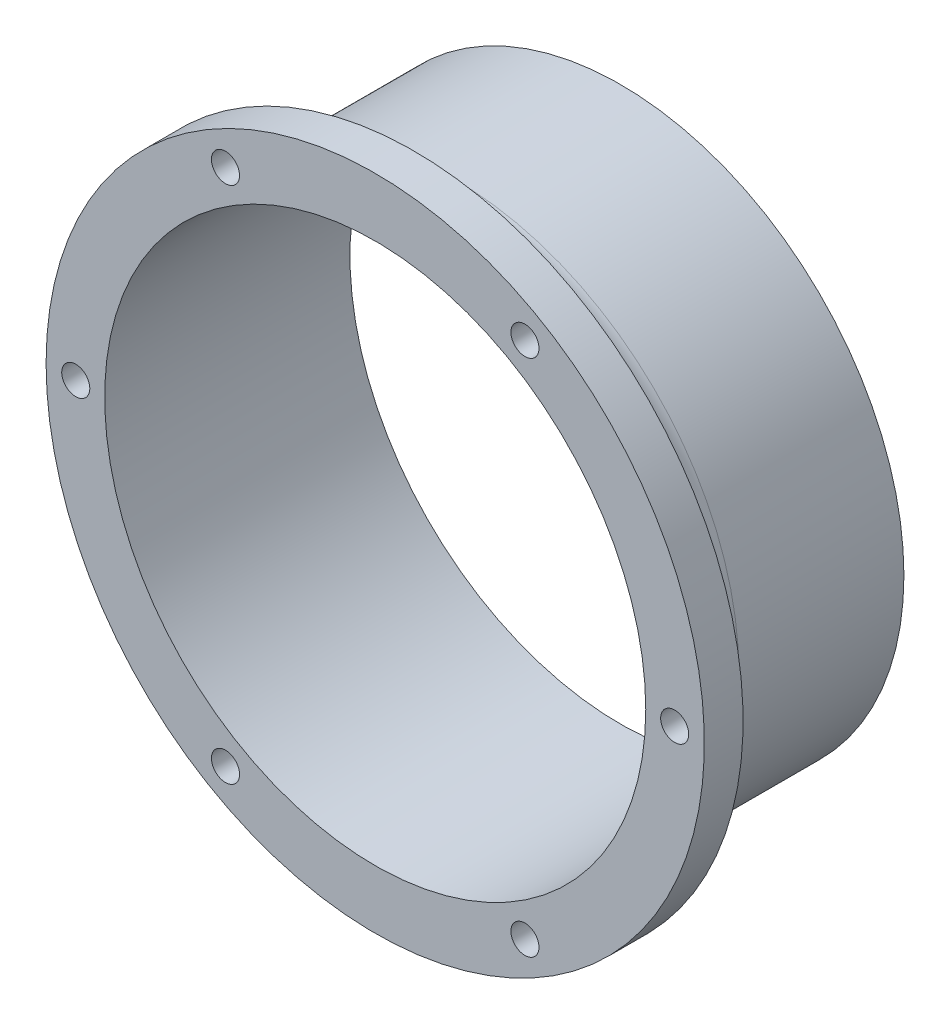
SolidWorks part; units mm, degrees
material "6061-T6 (SS)"
ref_plane "Front Plane" through (0, 0, 0) normal (0, 0, 1) x (1, 0, 0)
ref_plane "Top Plane" through (0, 0, 0) normal (0, 1, 0) x (1, 0, 0)
ref_plane "Right Plane" through (0, 0, 0) normal (1, 0, 0) x (0, 0, -1)
sketch "Sketch1" plane through (0, 0, 0) normal (0, 0, 1) x (1, 0, 0)
  circle A0 centre (0, 0) radius 34.8615
  circle A1 centre (0, 0) radius 33.274
  dimension "D1" = 69.723
  dimension "D2" = 1.5875
extrude "Boss-Extrude1" add sketch "Sketch1" along normal blind 25.4
sketch "Sketch2" plane through (0, 0, 25.4) normal (0, 0, 1) x (1, 0, 0)
  circle A0 centre (0, 0) radius 33.274
  circle A1 centre (0, 0) radius 40.4813
  circle A2 centre (0, 0) radius 33.274 construction
  dimension "D1" = 80.9625
extrude "Boss-Extrude2" add sketch "Sketch2" along normal blind 4.7625
fillet "Fillet1" radius 5.08 1 edges at (34.8615, 0, 25.4)
sketch "Sketch3" plane through (0, 0, 30.1625) normal (0, 0, 1) x (1, 0, 0)
  circle A0 centre (0, 0) radius 35.56
  dimension "D1" = 71.12
sketch "Sketch4" plane through (0, 0, 30.1625) normal (0, 0, 1) x (1, 0, 0)
  circle A0 centre (0, 0) radius 36.83 construction
  dimension "D1" = 73.66
hole_wizard "#8-32 Tapped Hole1" positions "Sketch6" profile "Sketch7" tap size "#8-32" standard "Ansi Inch"
sketch "Sketch6" plane through (0, 0, 30.1625) normal (0, 0, 1) x (1, 0, 0)
  line L0 (0, 0) -> (0, 47.1812) construction
  line L2 (0, 0) -> (-18.415, 31.8957) construction
  circle A0 centre (0, 0) radius 36.83 construction
  point P0 (-18.415, 31.8957)
  dimension "D1" = 30
sketch "Sketch7" plane through (-18.415, 31.8957, 30.1625) normal (1, 0, 0) x (0, -1, 0)
  line L0 (0, 0) -> (0, 11.7058)
  line L1 (0, 11.7058) -> (1.7272, 10.668)
  line L2 (1.7272, 10.668) -> (1.7272, 0)
  line L5 (1.7272, 0) -> (0, 0)
  line L10 (0, 11.7058) -> (-1.7272, 10.668) construction
  line L11 (0, -6.35) -> (0, 107.95) construction
  dimension "Tap Drill Dia." = 3.4544
  dimension "Tap Drill Depth" = 10.668
  dimension "Drill Angle" = 118
cosmetic thread "Hole Thread1" parameters "D1"=8.382, "D2"=4.1656
pattern_circular "CirPattern1" count 6 over 360 about axis through (0, 0, 0) along (0, 0, 1) of "#8-32 Tapped Hole1"
